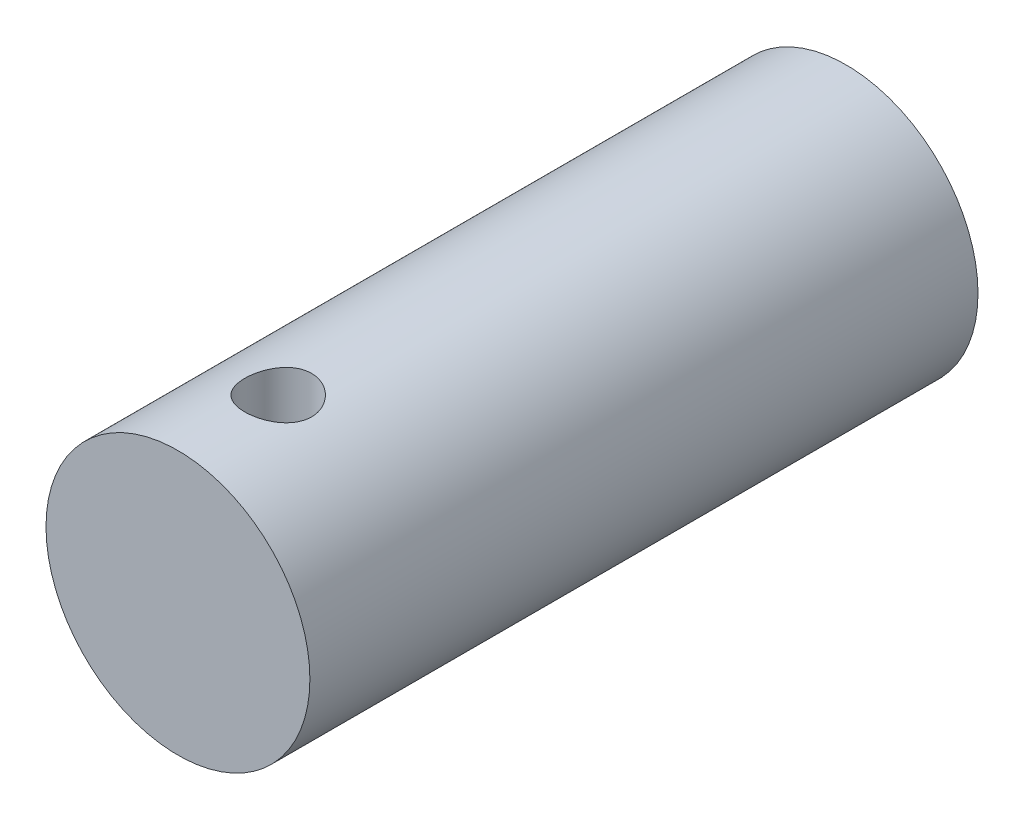
SolidWorks part; units mm, degrees
material "AISI 304"
ref_plane "Front" through (0, 0, 0) normal (0, 0, 1) x (1, 0, 0)
ref_plane "Top" through (0, 0, 0) normal (0, 1, 0) x (1, 0, 0)
ref_plane "Right" through (0, 0, 0) normal (1, 0, 0) x (0, 0, -1)
sketch "Sketch1" plane through (0, 0, 0) normal (0, 0, 1) x (1, 0, 0)
  circle A0 centre (0, 0) radius 3.95
  dimension "D1" = 7.9
extrude "Boss-Extrude1" add sketch "Sketch1" along normal blind 20
ref_plane "Plane1" through (0, 3.95, 0) normal (0, 1, 0) x (1, 0, 0)
sketch "Sketch2" plane through (0, 3.95, 0) normal (0, 1, 0) x (1, 0, 0)
  line L0 (-3.95, -20) -> (3.95, -20) construction
  circle A0 centre (0, -17) radius 1
  dimension "D1" = 2
  dimension "D2" = 3
extrude "Cut-Extrude1" cut sketch "Sketch2" against normal blind 25
